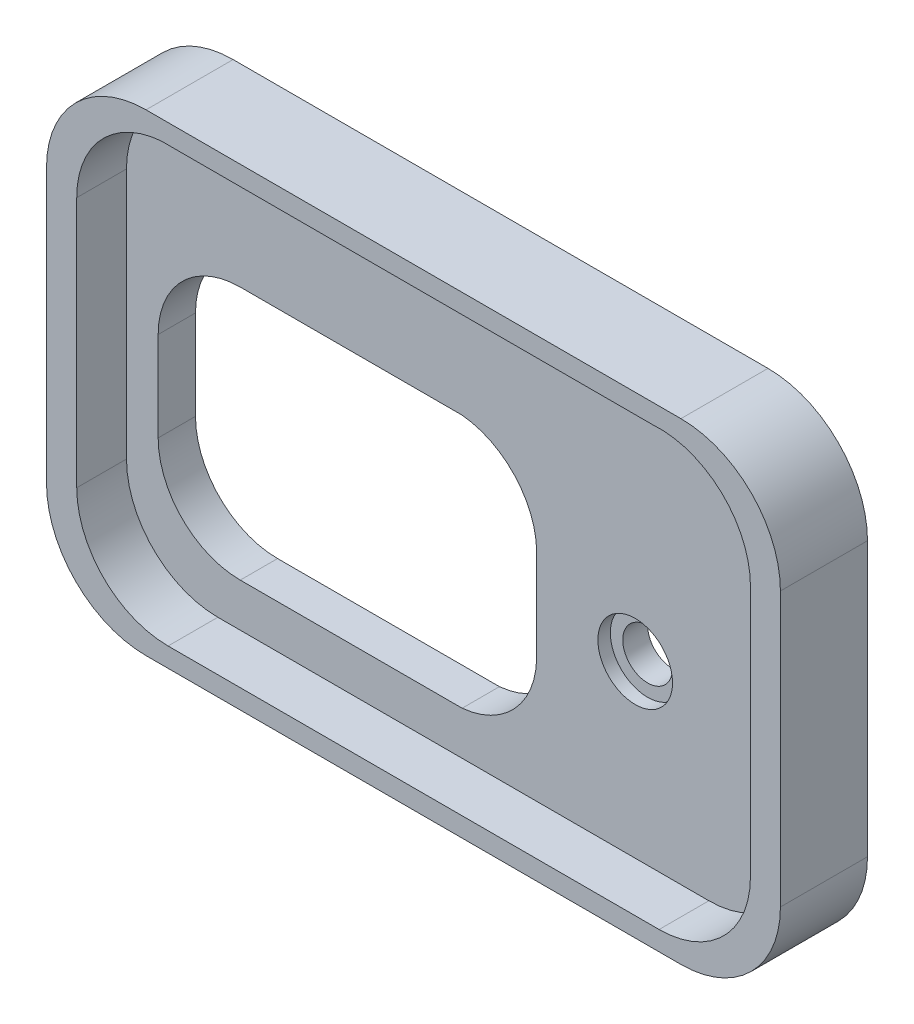
SolidWorks part; units mm, degrees
ref_plane "Front Plane" through (0, 0, 0) normal (0, 0, 1) x (1, 0, 0)
ref_plane "Top Plane" through (0, 0, 0) normal (0, 1, 0) x (1, 0, 0)
ref_plane "Right Plane" through (0, 0, 0) normal (1, 0, 0) x (0, 0, -1)
sketch "Sketch1" plane through (0, 0, 0) normal (0, 0, 1) x (1, 0, 0)
  line L1 (0, 0) -> (37.465, 0)
  line L2 (0, 0) -> (0, 24.13)
  line L3 (0, 24.13) -> (37.465, 24.13)
  line L4 (37.465, 0) -> (37.465, 24.13)
  dimension "D1" = 24.13
  dimension "D2" = 37.465
extrude "Boss-Extrude1" add sketch "Sketch1" along normal blind 4.445
sketch "Sketch2" plane through (0, 0, 4.445) normal (0, 0, 1) x (1, 0, 0)
  line L0 (37.465, 12.065) -> (35.5918, 12.065)
  line L1 (18.7325, 24.13) -> (18.7325, 22.9235)
  line L2 (0, 12.065) -> (1.8733, 12.065)
  line L3 (18.7325, 0) -> (18.7325, 1.2065)
  line L4 (3.175, 7.493) -> (3.175, 16.637)
  line L5 (7.493, 20.955) -> (29.972, 20.955)
  line L6 (34.29, 16.637) -> (34.29, 7.493)
  line L7 (29.972, 3.175) -> (7.493, 3.175)
  line L8 (0, 24.13) -> (0, 0) construction
  line L9 (37.465, 24.13) -> (0, 24.13) construction
  line L10 (0, 24.13) -> (0, 0)
  line L11 (37.465, 24.13) -> (0, 24.13)
  line L12 (7.1548, 20.955) -> (29.6338, 20.955)
  line L13 (34.29, 16.637) -> (34.29, 7.493)
  line L14 (29.972, 3.175) -> (7.493, 3.175)
  line L15 (3.175, 7.493) -> (3.175, 16.637)
  line L16 (18.9016, 24.13) -> (18.9016, 22.9235) construction
  line L17 (0, 12.065) -> (1.8733, 12.065) construction
  line L18 (37.465, 5.08) -> (37.465, 19.05)
  line L19 (33.0615, 24.13) -> (4.7418, 24.13)
  line L20 (0, 19.05) -> (0, 5.08)
  line L21 (5.2491, 0) -> (32.5541, 0.0113)
  line L22 (6.4453, 1.2065) -> (31.0198, 1.2065)
  line L23 (35.5918, 5.7785) -> (35.5918, 18.3515)
  line L24 (30.6815, 22.9235) -> (6.107, 22.9235)
  line L25 (1.8733, 18.3515) -> (1.8733, 5.7785)
  line L26 (37.465, 0) -> (37.465, 24.13) construction
  line L27 (18.9016, 1.2065) -> (18.9016, 0.0056) construction
  line L28 (35.5918, 12.065) -> (37.465, 12.065) construction
  arc A0 (29.972, 20.955) -> (34.29, 16.637) centre (29.972, 16.637) cw
  arc A1 (34.29, 7.493) -> (29.972, 3.175) centre (29.972, 7.493) cw
  arc A2 (7.493, 3.175) -> (3.175, 7.493) centre (7.493, 7.493) cw
  arc A3 (3.175, 16.637) -> (7.493, 20.955) centre (7.493, 16.637) cw
  arc A4 (34.29, 16.637) -> (29.6338, 20.955) centre (29.972, 16.6503) ccw
  arc A5 (29.972, 3.175) -> (34.29, 7.493) centre (29.972, 7.493) ccw
  arc A6 (3.175, 7.493) -> (7.493, 3.175) centre (7.493, 7.493) ccw
  arc A7 (7.1548, 20.955) -> (3.175, 16.637) centre (7.493, 16.6503) ccw
  arc A8 (37.465, 19.05) -> (33.0615, 24.13) centre (32.3852, 19.0952) ccw
  arc A9 (4.7418, 24.13) -> (0, 19.05) centre (5.08, 19.0613) ccw
  arc A10 (0, 5.08) -> (5.2491, 0) centre (5.08, 5.0772) ccw
  arc A11 (32.5541, 0.0113) -> (37.465, 5.08) centre (32.385, 5.0885) ccw
  arc A12 (6.107, 22.9235) -> (1.8733, 18.3515) centre (6.4452, 18.364) ccw
  arc A13 (1.8733, 5.7785) -> (6.4453, 1.2065) centre (6.4453, 5.7785) ccw
  arc A14 (35.5918, 18.3515) -> (30.6815, 22.9235) centre (31.0198, 18.364) ccw
  arc A15 (31.0198, 1.2065) -> (35.5918, 5.7785) centre (31.0198, 5.7785) ccw
  point P11 (3.175, 12.065)
  dimension "D3" = 4.318
  dimension "D12" = 5.08
  dimension "D13" = 5.08
  dimension "D14" = 5.08
  dimension "D15" = 5.08
  dimension "D4" = 17.78
  dimension "D5" = 31.115
  dimension "D10" = 1.2065
  dimension "D11" = 1.8732
  dimension "D16" = 13.97
  dimension "D17" = 13.97
  dimension "D18" = 27.305
extrude "Cut-Extrude2" cut sketch "Sketch2" against normal blind 2.54 contours L22 A15 L23 A14 L24 A12 L25 A13 A7 L12 L5 A4 L6 A1 L7 A2 L4 | A3 L4 A2 L7 A1 L6 A0 L5 | L12 A7 A3 | A0 A4 L5
fillet "Fillet1" radius 5.08 4 edges at (37.465, 24.13, 2.2225) (37.465, 0, 2.2225) (0, 0, 2.2225) (0, 24.13, 2.2225)
sketch "Sketch3" plane through (0, 0, 1.905) normal (0, 0, 1) x (1, 0, 0)
  line L0 (20.3901, 8.5258) -> (20.8175, 10.8382)
  line L1 (16.1777, 15.4192) -> (9.8512, 15.4014)
  line L2 (5.1247, 10.9098) -> (5.4787, 8.4542)
  line L3 (10.296, 4.0601) -> (15.7329, 3.9625)
  line L4 (7.3509, 16.159) -> (18.678, 16.159)
  line L5 (22.4639, 11.5628) -> (22.4639, 7.8011)
  line L6 (7.3509, 3.205) -> (18.678, 3.205)
  line L7 (3.1599, 11.968) -> (3.1599, 7.396)
  line L8 (13.0144, 16.159) -> (13.0144, 3.205) construction
  line L9 (3.1599, 9.682) -> (22.4639, 9.682) construction
  line L10 (5.3017, 9.682) -> (20.6038, 9.682) construction
  line L11 (13.0144, 15.4103) -> (13.0144, 4.0113) construction
  arc A0 (18.678, 16.159) -> (22.4639, 11.5628) centre (18.2729, 11.968) cw
  arc A1 (18.678, 3.205) -> (22.4639, 7.8011) centre (18.2729, 7.396) ccw
  arc A2 (3.1599, 7.396) -> (7.3509, 3.205) centre (7.3509, 7.396) ccw
  arc A3 (7.3509, 16.159) -> (3.1599, 11.968) centre (7.3509, 11.968) ccw
  spline S0 degree 2 poles (20.8175, 10.8382) (20.82, 10.9908) (20.8004, 11.3402) (20.7305, 11.8546) (20.4376, 12.8472) (19.5293, 14.1968) (18.1669, 15.0756) (17.1627, 15.3498) (16.6574, 15.409) (16.3028, 15.4216) (16.1777, 15.4192) knots 0 0 0 0.046875 0.09375 0.1875 0.375 0.625 0.8125 0.90625 0.953125 1 1 1
  spline S1 degree 2 poles (9.8512, 15.4014) (9.7263, 15.4062) (9.3701, 15.4003) (8.8583, 15.3498) (7.8502, 15.0933) (6.4708, 14.2372) (5.5408, 12.9075) (5.2293, 11.9156) (5.1513, 11.4096) (5.1252, 11.0626) (5.1247, 10.9098) knots 0 0 0 0.046875 0.09375 0.1875 0.375 0.625 0.8125 0.90625 0.953125 1 1 1
  spline S2 degree 2 poles (5.4787, 8.4542) (5.4823, 8.3016) (5.5157, 7.9533) (5.6058, 7.442) (5.9378, 6.4617) (6.8987, 5.1491) (8.2948, 4.3249) (9.309, 4.0905) (9.8163, 4.0514) (10.1711, 4.0528) (10.296, 4.0601) knots 0 0 0 0.046875 0.09375 0.1875 0.375 0.625 0.8125 0.90625 0.953125 1 1 1
  spline S3 degree 2 poles (15.7329, 3.9625) (15.8578, 3.9596) (16.2138, 3.9709) (16.7248, 4.0292) (17.7289, 4.301) (19.095, 5.1782) (20.0047, 6.5219) (20.301, 7.5185) (20.3712, 8.0256) (20.392, 8.373) (20.3901, 8.5258) knots 0 0 0 0.046875 0.09375 0.1875 0.375 0.625 0.8125 0.90625 0.953125 1 1 1
extrude "Cut-Extrude4" cut sketch "Sketch3" against normal blind 2.54 contours L4 A0 L5 A1 L6 A2 L7 A3
sketch "Sketch4" plane through (0, 0, 1.905) normal (0, 0, 1) x (1, 0, 0)
  line L0 (22.4639, 9.682) -> (34.8414, 9.682) construction
  line L1 (23.3842, 17.5759) -> (23.3842, 1.8039)
  line L2 (22.4639, 11.5628) -> (22.4639, 7.8011) construction
  line L3 (31.6392, 1.8039) -> (23.3842, 1.8039)
  line L4 (23.3842, 17.5759) -> (31.6392, 17.5759)
  line L5 (31.6392, 17.5759) -> (31.6392, 1.8039)
  line L6 (27.5117, 17.5759) -> (27.5117, 1.8039) construction
  circle A0 centre (27.5117, 9.6899) radius 1.27
  point P5 (29.5303, 7.3913)
extrude "Cut-Extrude5" cut sketch "Sketch4" against normal blind 2.54 contours A0
sketch "Sketch5" plane through (0, 0, 1.905) normal (0, 0, 1) x (1, 0, 0)
  circle A0 centre (27.5117, 9.6899) radius 1.27 construction
  circle A1 centre (27.5117, 9.6899) radius 1.27
  circle A2 centre (27.5117, 9.6899) radius 1.905
  dimension "D1" = 3.81
extrude "Cut-Extrude6" cut sketch "Sketch5" against normal blind 0.635
sketch "Sketch6" plane through (0, 0, 4.445) normal (0, 0, 1) x (1, 0, 0)
  line L0 (1.8733, 12.065) -> (35.5918, 12.065) construction
  line L1 (18.3943, 22.9235) -> (18.3943, 1.2065) construction
  line L2 (1.5428, 18.4772) -> (1.5428, 5.6528)
  line L3 (6.2063, 0.9893) -> (31.2723, 0.9893)
  line L4 (6.4453, 1.2065) -> (31.0198, 1.2065)
  line L5 (35.5918, 5.7785) -> (35.5918, 18.3515)
  line L6 (30.6815, 22.9235) -> (6.107, 22.9235)
  line L7 (1.8732, 18.3515) -> (1.8733, 5.7785)
  line L8 (6.4453, 1.2065) -> (31.0198, 1.2065)
  line L9 (35.5918, 5.7785) -> (35.5918, 18.3515)
  line L10 (30.6815, 22.9235) -> (6.107, 22.9235)
  line L11 (1.8732, 18.3515) -> (1.8733, 5.7785)
  line L12 (35.9357, 5.6528) -> (35.9357, 18.4772)
  line L13 (30.9273, 23.1407) -> (5.8613, 23.1407)
  arc A0 (31.2723, 0.9893) -> (35.9357, 5.6528) centre (31.2723, 5.6528) ccw
  arc A1 (35.9357, 18.4772) -> (30.9273, 23.1407) centre (31.2723, 18.49) ccw
  arc A2 (1.5428, 5.6528) -> (6.2063, 0.9893) centre (6.2063, 5.6528) ccw
  arc A3 (5.8613, 23.1407) -> (1.5428, 18.4772) centre (6.2063, 18.49) ccw
  arc A4 (31.0198, 1.2065) -> (35.5918, 5.7785) centre (31.0198, 5.7785) ccw
  arc A5 (35.5918, 18.3515) -> (30.6815, 22.9235) centre (31.0198, 18.364) ccw
  arc A6 (6.107, 22.9235) -> (1.8732, 18.3515) centre (6.4452, 18.364) ccw
  arc A7 (1.8733, 5.7785) -> (6.4453, 1.2065) centre (6.4453, 5.7785) ccw
  arc A8 (31.0198, 1.2065) -> (35.5918, 5.7785) centre (31.0198, 5.7785) ccw
  arc A9 (35.5918, 18.3515) -> (30.6815, 22.9235) centre (31.0198, 18.364) ccw
  arc A10 (6.107, 22.9235) -> (1.8732, 18.3515) centre (6.4452, 18.364) ccw
  arc A11 (1.8733, 5.7785) -> (6.4453, 1.2065) centre (6.4453, 5.7785) ccw
  dimension "D1" = 0
extrude "Cut-Extrude7" cut sketch "Sketch6" against normal up to surface (2.54 mm away) up to face at (29.4167, 9.6899, 1.905)
